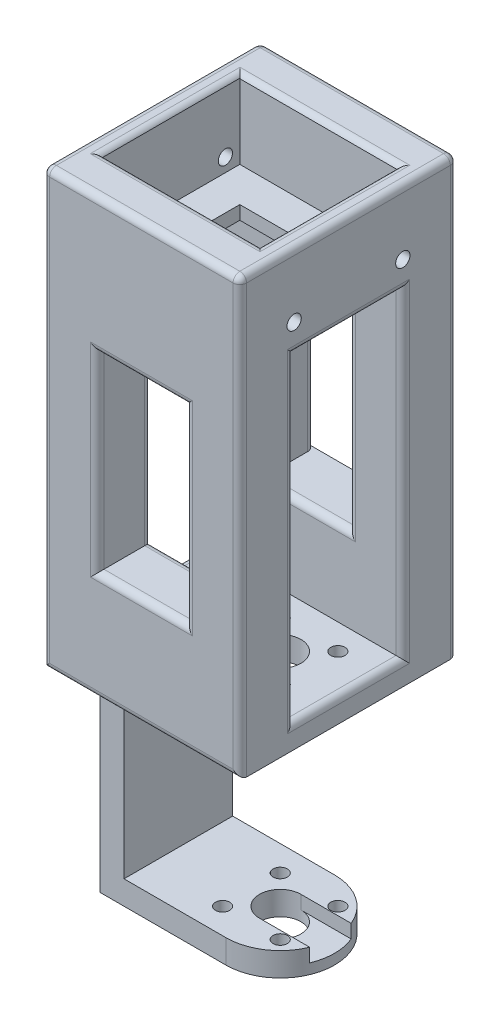
SolidWorks part; units mm, degrees
ref_plane "前视基准面" through (0, 0, 0) normal (0, 0, 1) x (1, 0, 0)
ref_plane "上视基准面" through (0, 0, 0) normal (0, 1, 0) x (1, 0, 0)
ref_plane "右视基准面" through (0, 0, 0) normal (1, 0, 0) x (0, 0, -1)
sketch "草图1" plane through (0, 0, 0) normal (0, 1, 0) x (1, 0, 0)
  line L0 (0, 8) -> (-15, 8)
  line L1 (0, 0) -> (-20.7875, 0) construction
  line L2 (0, -8) -> (-15, -8)
  line L3 (-15, 8) -> (-15, -8)
  line L4 (0, 8) -> (0, -13.8508) construction
  line L5 (0, 0) -> (-10.1753, 10.1753) construction
  line L6 (0, 0) -> (-6.4674, -6.4674) construction
  line L7 (4.2426, 4.2426) -> (-5.3918, -5.3918) construction
  arc A0 (0, -8) -> (0, 8) centre (0, 0) ccw
  circle A1 centre (0, 0) radius 6 construction
  circle A6 centre (0, 0) radius 3.05
  circle A7 centre (-4.2426, 4.2426) radius 1.05
  circle A9 centre (-4.2426, -4.2426) radius 1.05
  circle A10 centre (4.2426, -4.2426) radius 1.05
  circle A11 centre (4.2426, 4.2426) radius 1.05
  dimension "D1" = 16
  dimension "D3" = 12
  dimension "D8" = 6.1
  dimension "D10" = 2.1
  dimension "D13" = 2.1
  dimension "D2" = 15
  dimension "D9" = 45
  dimension "D12" = 45
extrude "凸台-拉伸1" add sketch "草图1" along normal blind 3.5
ref_plane "基准面4" through (0, 18, 0) normal (0, 1, 0) x (1, 0, 0)
mirror "镜向4" about plane through (0, 18, 0) normal (0, 1, 0) of bodies 101
sketch "草图2" plane through (-15, 0, 0) normal (-1, 0, 0) x (0, 0, 1)
  line L0 (-8, 0) -> (8, 0) construction
  line L1 (-8, 36) -> (8, 36)
  line L2 (-8, 36) -> (-8, 0)
  line L3 (-8, 0) -> (8, 0)
  line L4 (8, 36) -> (8, 0)
  line L5 (8, 3.5) -> (8, 0) construction
extrude "凸台-拉伸2" add sketch "草图2" along normal blind 3.5
sketch "草图3" plane through (0, 3.5, 0) normal (0, 1, 0) x (1, 0, 0)
  line L0 (0, -8) -> (10.05, -8)
  line L1 (0, 8) -> (10.05, 8)
  line L2 (10.05, -8) -> (10.05, 8)
  line L3 (0, 8) -> (-15, 8)
  line L4 (-15, 8) -> (-15, -8)
  line L5 (-15, -8) -> (0, -8)
  arc A1 (0, -8) -> (0, 8) centre (0, 0) ccw
  arc A2 (0, -8) -> (0, 8) centre (0, 0) ccw
  dimension "D2" = 25.05
  dimension "D3" = 25.05
  dimension "D1" = 0
sketch "草图4" plane through (0, 32.5, 0) normal (0, -1, 0) x (1, 0, 0)
  line L0 (0, -8) -> (10.05, -8) construction
  line L1 (10.05, 8) -> (10.05, -8) construction
  line L2 (0, 8) -> (10.05, 8) construction
  line L3 (0, 8) -> (10.05, 8)
  line L4 (10.05, 8) -> (10.05, -8)
  line L5 (0, -8) -> (10.05, -8)
  arc A0 (0, -8) -> (0, 8) centre (0, 0) ccw construction
  arc A1 (0, -8) -> (0, 8) centre (0, 0) ccw
extrude "凸台-拉伸4" add sketch "草图4" against normal blind 3.5
sketch "草图5" plane through (0, 0, 8) normal (0, 0, 1) x (1, 0, 0)
  line L1 (10.05, 32.5) -> (-18.5, 32.5)
  line L2 (-18.5, 0) -> (-18.5, 36) construction
  line L4 (-18.5, 96.5) -> (10.05, 96.5)
  line L5 (10.05, 96.5) -> (10.05, 32.5)
  line L6 (-18.95, 96.5) -> (-18.95, 32.5)
  line L7 (-18.95, 96.5) -> (-18.5, 96.5)
  line L8 (-18.95, 32.5) -> (-18.5, 32.5)
  dimension "D1" = 64
extrude "凸台-拉伸5" add sketch "草图5" along normal blind 8
ref_plane "基准面5" through (0, 0, 0) normal (0, 0, 1) x (1, 0, 0)
mirror "镜向5" about plane through (0, 0, 0) normal (0, 0, 1) of "凸台-拉伸5"
sketch "草图6" plane through (10.05, 0, 0) normal (1, 0, 0) x (0, 0, -1)
  line L0 (-8, 96.5) -> (-8, 85)
  line L1 (-8, 36) -> (-8, 96.5) construction
  line L2 (-8, 96.5) -> (-10.03, 96.5)
  line L4 (-16, 96.5) -> (-8, 96.5) construction
  line L5 (-10.03, 96.5) -> (-10.03, 85)
  line L6 (-10.03, 85) -> (-8, 85)
  line L7 (0, 10.175) -> (0, -10.175) construction
  line L8 (10.03, 85) -> (8, 85)
  line L9 (10.03, 96.5) -> (10.03, 85)
  line L10 (8, 96.5) -> (10.03, 96.5)
  line L11 (8, 96.5) -> (8, 85)
  dimension "D1" = 11.5
  dimension "D2" = 2.03
extrude "切除-拉伸1" cut sketch "草图6" against normal up to next
sketch "草图7" plane through (0, 0, 10.03) normal (0, 0, -1) x (-1, 0, 0)
  line L0 (18.95, 85) -> (-10.05, 85) construction
  line L1 (18.95, 85) -> (15.95, 85)
  line L2 (-10.05, 96.5) -> (-7.05, 96.5)
  line L3 (-10.05, 96.5) -> (18.95, 96.5) construction
  line L4 (-7.05, 96.5) -> (-7.05, 85)
  line L5 (-10.05, 96.5) -> (-10.05, 85)
  line L6 (18.95, 96.5) -> (15.95, 96.5)
  line L7 (15.95, 96.5) -> (15.95, 85)
  line L8 (18.95, 96.5) -> (18.95, 85)
  line L9 (-7.05, 85) -> (-10.05, 85)
  dimension "D1" = 3
  dimension "D2" = 3
extrude "凸台-拉伸6" add sketch "草图7" along normal up to next
sketch "草图8" plane through (0, 0, -8) normal (0, 0, 1) x (1, 0, 0)
  line L2 (-18.5, 36) -> (-18.5, 32.5)
  line L3 (-18.5, 36) -> (-18.95, 36)
  line L4 (-18.95, 96.5) -> (-18.95, 32.5) construction
  line L5 (-18.95, 36) -> (-18.95, 32.5)
  line L6 (-18.95, 32.5) -> (-18.5, 32.5)
extrude "凸台-拉伸7" add sketch "草图8" along normal up to next
sketch "草图9" plane through (0, 0, -8) normal (0, 0, 1) x (1, 0, 0)
  line L0 (10.05, 32.5) -> (10.05, 96.5) construction
  line L1 (-18.95, 85) -> (10.05, 85)
  line L2 (-18.95, 85) -> (-18.95, 83)
  line L3 (-18.95, 83) -> (10.05, 83)
  line L4 (10.05, 85) -> (10.05, 83)
  dimension "D1" = 2
extrude "凸台-拉伸8" add sketch "草图9" along normal up to next
sketch "草图10" plane through (-15.95, 0, 0) normal (1, 0, 0) x (0, 0, -1)
  line L0 (10.03, 85) -> (-10.03, 85) construction
  line L1 (10.03, 85) -> (-10.03, 85) construction
  line L2 (-10.03, 96.5) -> (-10.03, 85) construction
  line L3 (10.03, 96.5) -> (10.03, 85) construction
  line L4 (-10.03, 96.5) -> (-10.03, 85) construction
  line L5 (10.03, 96.5) -> (10.03, 85) construction
  line L6 (0, 85) -> (0, 101.7166) construction
  circle A0 centre (-8, 87) radius 1.05
  circle A1 centre (8, 87) radius 1.05
  dimension "D3" = 2.1
  dimension "D1" = 16
  dimension "D2" = 2
extrude "切除-拉伸2" cut sketch "草图10" along normal mid plane 63.5
sketch "草图12" plane through (0, 3.5, 0) normal (0, 1, 0) x (1, 0, 0)
  line L0 (0, 3.05) -> (11.7827, 3.05)
  line L1 (0, -3.05) -> (11.7827, -3.05)
  line L2 (11.7827, 3.05) -> (11.7827, -3.05)
  circle A0 centre (0, 0) radius 3.05 construction
  arc A1 (0, -3.05) -> (0, 3.05) centre (0, 0) ccw
extrude "切除-拉伸3" cut sketch "草图12" against normal blind 2
sketch "草图13" plane through (0, 83, 0) normal (0, -1, 0) x (1, 0, 0)
  line L0 (-18.5, 8) -> (0, 8) construction
  line L1 (-10.95, 5) -> (0.05, 5)
  line L2 (-10.95, 5) -> (-10.95, -5)
  line L3 (-10.95, -5) -> (0.05, -5)
  line L4 (0.05, 5) -> (0.05, -5)
  line L5 (0, -8) -> (-18.5, -8) construction
  line L6 (-18.95, 16) -> (-18.95, -16) construction
  line L7 (10.05, 8) -> (10.05, -8) construction
  dimension "D1" = 3
  dimension "D2" = 3
  dimension "D3" = 8
  dimension "D4" = 10
extrude "切除-拉伸4" cut sketch "草图13" against normal up to next
sketch "草图14" plane through (0, 0, -16) normal (0, 0, -1) x (-1, 0, 0)
  line L0 (-10.05, 32.5) -> (-10.05, 96.5) construction
  line L1 (-2.05, 76.5) -> (10.95, 76.5)
  line L2 (-2.05, 76.5) -> (-2.05, 48.5)
  line L3 (-2.05, 48.5) -> (10.95, 48.5)
  line L4 (10.95, 76.5) -> (10.95, 48.5)
  line L5 (18.95, 96.5) -> (18.95, 32.5) construction
  line L6 (18.95, 32.5) -> (-10.05, 32.5) construction
  line L7 (-10.05, 96.5) -> (18.95, 96.5) construction
  dimension "D1" = 8
  dimension "D2" = 8
  dimension "D3" = 16
  dimension "D4" = 20
extrude "切除-拉伸5" cut sketch "草图14" against normal through all
fillet "圆角1" radius 1 36 edges at (-4.45, 96.5, -16) (10.05, 64.5, -16) (-4.45, 32.5, -16) (-18.95, 64.5, -16) (-4.45, 96.5, 10.03) (-4.45, 96.5, -10.03) (-15.95, 96.5, 0) (7.05, 96.5, 0) (-18.95, 36, 0) (-18.95, 59.5, 8) (-18.95, 59.5, -8) (-18.95, 83, 0) (10.05, 83, 0) (2.05, 62.5, 8) (2.05, 62.5, -8) (2.05, 62.5, 16) (-4.45, 76.5, 8) (-4.45, 76.5, -8) (-4.45, 76.5, 16) (-10.95, 62.5, 8) (-10.95, 62.5, -8) (-10.95, 62.5, 16) (-4.45, 48.5, 8) (-4.45, 48.5, -8) (-4.45, 48.5, 16) (-10.95, 62.5, -16) (-4.45, 76.5, -16) (10.05, 36, 0) (-18.95, 96.5, 0) (10.05, 59.5, 8) (10.05, 96.5, 0) (-4.45, 96.5, 16) (-18.95, 64.5, 16) (-4.45, 32.5, 16) (10.05, 64.5, 16) (10.05, 59.5, -8)
ref_plane "基准面6" through (-4.45, 0, 0) normal (-1, 0, 0) x (0, 0, 1)
sketch "草图15" plane through (7.05, 0, 0) normal (-1, 0, 0) x (0, 0, 1)
  line L4 (10.03, 85) -> (10.03, 95.5)
  line L5 (10.03, 95.5) -> (-10.03, 95.5)
  line L6 (-10.03, 95.5) -> (-10.03, 85)
  line L7 (-10.03, 85) -> (10.03, 85)
  line L8 (10.03, 85) -> (10.03, 95.5)
  line L9 (10.03, 95.5) -> (-10.03, 95.5)
  line L10 (-10.03, 95.5) -> (-10.03, 85)
  line L11 (-10.03, 85) -> (10.03, 85)
  dimension "D1" = 0
sketch "草图16" plane through (-4.45, 0, 0) normal (-1, 0, 0) x (0, 0, 1)
  line L0 (-10.03, 95.5) -> (-10.03, 98.3607)
  line L1 (-10.03, 98.3607) -> (10.03, 98.3607)
  line L2 (10.03, 98.3607) -> (10.03, 95.5)
  line L4 (10.03, 85) -> (10.03, 95.5)
  line L5 (10.03, 95.5) -> (-10.03, 95.5)
  line L6 (-10.03, 95.5) -> (-10.03, 85)
  line L7 (-10.03, 85) -> (10.03, 85)
  line L8 (10.03, 85) -> (10.03, 95.5)
  line L10 (-10.03, 95.5) -> (-10.03, 85)
  line L11 (-10.03, 85) -> (10.03, 85)
  dimension "D1" = 0
extrude "切除-拉伸6" cut sketch "草图16" against normal mid plane 23.25
ref_plane "基准面7" through (0, 0, 0) normal (0, 0, 1) x (1, 0, 0)
sketch "草图17" plane through (0, 0, 0) normal (0, 0, 1) x (1, 0, 0)
  line L0 (-16.075, 95.9841) -> (-15.9137, 99.2044)
  line L1 (-15.9137, 99.2044) -> (7.175, 98.0481)
  line L2 (7.175, 98.0481) -> (7.175, 95.9841)
  line L4 (-16.075, 85) -> (7.175, 85)
  line L5 (7.175, 85) -> (7.175, 95.9841)
  line L6 (7.05, 95.5) -> (-15.95, 95.5)
  line L7 (-16.075, 95.9841) -> (-16.075, 85)
  line L8 (-16.075, 85) -> (7.175, 85)
  line L9 (7.175, 85) -> (7.175, 95.9841)
  line L11 (-16.075, 95.9841) -> (-16.075, 85)
  arc A2 (7.175, 95.9841) -> (7.05, 95.5) centre (8.05, 95.5) ccw
  arc A3 (-15.95, 95.5) -> (-16.075, 95.9841) centre (-16.95, 95.5) ccw
  dimension "D1" = 0
extrude "切除-拉伸7" cut sketch "草图17" against normal mid plane 20.25
ref_plane "基准面8" through (-4.45, 0, 0) normal (1, 0, 0) x (0, 0, -1)
sketch "草图19" plane through (-4.45, 0, 0) normal (1, 0, 0) x (0, 0, -1)
  line L0 (-10.125, 95.9841) -> (-10.125, 99.9657)
  line L1 (-10.125, 99.9657) -> (10.09, 99.9657)
  line L2 (10.09, 99.9657) -> (10.125, 95.9841)
  line L6 (10.125, 95.9841) -> (-10.125, 95.9841)
  line L8 (-10.125, 95.9841) -> (-10.125, 85)
  line L9 (-10.125, 85) -> (10.125, 85)
  line L10 (10.125, 85) -> (10.125, 95.9841)
  line L14 (-10.125, 95.9841) -> (-10.125, 85)
  line L15 (-10.125, 85) -> (10.125, 85)
  line L16 (10.125, 85) -> (10.125, 95.9841)
  dimension "D1" = 0
extrude "切除-拉伸8" cut sketch "草图19" against normal mid plane 23.1
